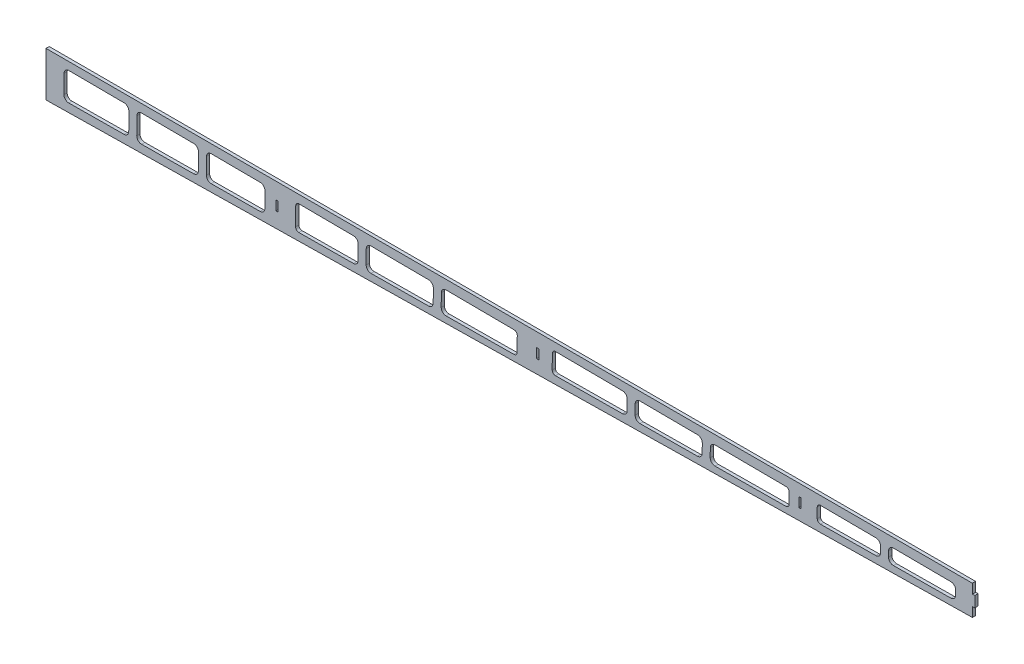
SolidWorks part; units mm, degrees
ref_plane "前视基准面" through (0, 0, 0) normal (0, 0, 1) x (1, 0, 0)
ref_plane "上视基准面" through (0, 0, 0) normal (0, 1, 0) x (1, 0, 0)
ref_plane "右视基准面" through (0, 0, 0) normal (1, 0, 0) x (0, 0, -1)
sketch "Model" plane through (0, 0, 0) normal (0, 0, 1) x (1, 0, 0)
  line L0 (785.4351, -35.5339) -> (785.4351, -41.4469)
  line L1 (786.9351, -41.4469) -> (786.9351, -48.1474)
  line L2 (786.9351, -48.1474) -> (785.4351, -48.1474)
  line L3 (206.6001, -35.5339) -> (206.6001, -63.4755)
  line L4 (350.2005, -45.6437) -> (350.2005, -51.6437)
  line L5 (513.2012, -44.1523) -> (513.2012, -50.1523)
  line L6 (676.9838, -42.8438) -> (676.9838, -48.8438)
  line L7 (206.6001, -35.5339) -> (351.5037, -35.5339)
  line L8 (351.5037, -35.5339) -> (514.2811, -35.5339)
  line L9 (514.2811, -35.5339) -> (677.8391, -35.5339)
  line L10 (677.8391, -35.5339) -> (785.4351, -35.5339)
  line L11 (206.6001, -63.4755) -> (785.4665, -54.0699)
  line L12 (786.9351, -41.4469) -> (785.4351, -41.4469)
  line L13 (676.9838, -42.8438) -> (678.4838, -42.8438)
  line L14 (678.4838, -42.8438) -> (678.4838, -48.8438)
  line L15 (676.9838, -48.8438) -> (678.4838, -48.8438)
  line L16 (513.2012, -44.1523) -> (514.7012, -44.1523)
  line L17 (514.7012, -44.1523) -> (514.7012, -50.1523)
  line L18 (513.2012, -50.1523) -> (514.7012, -50.1523)
  line L19 (350.2005, -45.6437) -> (351.7005, -45.6437)
  line L20 (351.7005, -45.6437) -> (351.7005, -51.6437)
  line L21 (350.2005, -51.6437) -> (351.7005, -51.6437)
  line L22 (255.3856, -40.6006) -> (220.8863, -40.3916)
  line L23 (255.3284, -57.6646) -> (220.8258, -57.9857)
  line L24 (343.3766, -44.1337) -> (343.3174, -53.8918)
  line L25 (217.8682, -43.3734) -> (217.7979, -54.9676)
  line L26 (266.3848, -40.6673) -> (298.8842, -40.8641)
  line L27 (266.3286, -57.5622) -> (298.831, -57.2598)
  line L28 (309.8832, -40.9308) -> (340.3948, -41.1156)
  line L29 (309.831, -57.1574) -> (340.3454, -56.8735)
  line L30 (364.652, -40.6438) -> (398.7222, -40.8811)
  line L31 (409.7112, -40.9577) -> (445.6232, -41.2078)
  line L32 (456.6128, -41.2844) -> (499.0688, -41.5801)
  line L33 (362.6382, -42.6298) -> (362.5578, -54.1645)
  line L34 (364.5764, -56.1783) -> (398.6668, -55.8602)
  line L35 (409.665, -55.7575) -> (445.5731, -55.4223)
  line L36 (456.5713, -55.3197) -> (499.0084, -54.9236)
  line L37 (501.0548, -43.594) -> (500.9897, -52.9376)
  line L38 (406.618, -55.8674) -> (406.6186, -55.7859)
  line L39 (524.9663, -40.4255) -> (566.7724, -40.7168)
  line L40 (577.7722, -40.7934) -> (613.674, -41.0435)
  line L41 (624.6738, -41.1201) -> (668.9628, -41.4286)
  line L42 (524.9077, -53.5082) -> (566.7407, -53.1177)
  line L43 (577.7416, -53.0151) -> (613.647, -52.6799)
  line L44 (624.6479, -52.5772) -> (668.9206, -52.164)
  line L45 (522.8891, -51.4943) -> (522.9524, -42.4115)
  line L46 (670.9488, -43.4425) -> (670.9019, -50.178)
  line L47 (690.4954, -40.8692) -> (725.1012, -41.1103)
  line L48 (736.095, -41.1869) -> (772.0021, -41.437)
  line L49 (690.4954, -51.0729) -> (725.0829, -50.7501)
  line L50 (736.0811, -50.6474) -> (771.9892, -50.3123)
  line L51 (688.4815, -42.8553) -> (688.4767, -49.0714)
  line L52 (774.9812, -44.4578) -> (774.9611, -47.3333)
  line L53 (785.4665, -54.0699) -> (785.4351, -48.1474)
  line L54 (258.3004, -54.6829) -> (258.3674, -43.6187)
  line L55 (263.3667, -43.649) -> (263.3007, -54.5442)
  line L56 (301.866, -43.8823) -> (301.803, -54.2781)
  line L57 (306.8032, -54.1394) -> (306.8651, -43.9125)
  line L58 (401.7012, -43.9019) -> (401.6387, -52.8812)
  line L59 (406.637, -52.7395) -> (406.6903, -43.9394)
  line L60 (448.6022, -44.2287) -> (448.545, -52.4434)
  line L61 (453.5433, -52.3017) -> (453.592, -44.2661)
  line L62 (569.7514, -43.7349) -> (569.7127, -50.1187)
  line L63 (574.7513, -43.7751) -> (574.7136, -49.997)
  line L64 (616.6531, -44.0616) -> (616.6189, -49.6982)
  line L65 (621.653, -44.1019) -> (621.6199, -49.5592)
  line L66 (728.0802, -44.1311) -> (728.0548, -47.7711)
  line L67 (733.0741, -44.1686) -> (733.0532, -47.6294)
  arc A0 (255.3284, -57.6646) -> (258.3004, -54.6829) centre (255.3004, -54.6647) ccw
  arc A1 (340.3454, -56.8735) -> (343.3174, -53.8918) centre (340.3175, -53.8736) ccw
  arc A2 (217.7979, -54.9676) -> (220.8258, -57.9857) centre (220.7979, -54.9858) ccw
  arc A3 (343.3766, -44.1337) -> (340.3948, -41.1156) centre (340.3766, -44.1156) ccw
  arc A4 (220.8863, -40.3916) -> (217.8682, -43.3734) centre (220.8681, -43.3916) ccw
  arc A5 (258.3674, -43.6187) -> (255.3856, -40.6006) centre (255.3675, -43.6006) ccw
  arc A6 (266.3848, -40.6673) -> (263.3667, -43.649) centre (266.3667, -43.6672) ccw
  arc A7 (298.831, -57.2598) -> (301.803, -54.2781) centre (298.8031, -54.2599) ccw
  arc A8 (301.866, -43.8823) -> (298.8842, -40.8641) centre (298.8661, -43.8641) ccw
  arc A9 (263.3007, -54.5442) -> (266.3286, -57.5622) centre (266.3007, -54.5624) ccw
  arc A10 (309.8832, -40.9308) -> (306.8651, -43.9125) centre (309.8651, -43.9307) ccw
  arc A11 (306.8032, -54.1394) -> (309.831, -57.1574) centre (309.8031, -54.1575) ccw
  arc A12 (364.652, -40.6438) -> (362.6382, -42.6298) centre (364.6381, -42.6437) ccw
  arc A13 (362.5578, -54.1645) -> (364.5764, -56.1783) centre (364.5578, -54.1784) ccw
  arc A14 (499.0084, -54.9236) -> (500.9897, -52.9376) centre (498.9898, -52.9237) ccw
  arc A15 (401.7012, -43.9019) -> (398.7222, -40.8811) centre (398.7013, -43.881) ccw
  arc A16 (398.6668, -55.8602) -> (401.6387, -52.8812) centre (398.6388, -52.8603) ccw
  arc A17 (409.7112, -40.9577) -> (406.6903, -43.9394) centre (409.6903, -43.9576) ccw
  arc A18 (406.637, -52.7395) -> (409.665, -55.7575) centre (409.637, -52.7576) ccw
  arc A19 (448.6022, -44.2287) -> (445.6232, -41.2078) centre (445.6023, -44.2078) ccw
  arc A20 (445.5731, -55.4223) -> (448.545, -52.4434) centre (445.5451, -52.4225) ccw
  arc A21 (456.6128, -41.2844) -> (453.592, -44.2661) centre (456.592, -44.2843) ccw
  arc A22 (453.5433, -52.3017) -> (456.5713, -55.3197) centre (456.5433, -52.3198) ccw
  arc A23 (501.0548, -43.594) -> (499.0688, -41.5801) centre (499.0549, -43.5801) ccw
  arc A24 (670.9488, -43.4425) -> (668.9628, -41.4286) centre (668.9488, -43.4286) ccw
  arc A25 (524.9663, -40.4255) -> (522.9524, -42.4115) centre (524.9523, -42.4255) ccw
  arc A26 (522.8891, -51.4943) -> (524.9077, -53.5082) centre (524.8891, -51.5083) ccw
  arc A27 (668.9206, -52.164) -> (670.9019, -50.178) centre (668.9019, -50.1641) ccw
  arc A28 (569.7514, -43.7349) -> (566.7724, -40.7168) centre (566.7515, -43.7167) ccw
  arc A29 (566.7407, -53.1177) -> (569.7127, -50.1187) centre (566.7127, -50.1179) ccw
  arc A30 (577.7722, -40.7934) -> (574.7513, -43.7751) centre (577.7513, -43.7933) ccw
  arc A31 (574.7136, -49.997) -> (577.7416, -53.0151) centre (577.7136, -50.0152) ccw
  arc A32 (613.647, -52.6799) -> (616.6189, -49.6982) centre (613.619, -49.6801) ccw
  arc A33 (616.6531, -44.0616) -> (613.674, -41.0435) centre (613.6531, -44.0434) ccw
  arc A34 (624.6738, -41.1201) -> (621.653, -44.1019) centre (624.6529, -44.12) ccw
  arc A35 (621.6199, -49.5592) -> (624.6479, -52.5772) centre (624.6199, -49.5774) ccw
  arc A36 (690.4954, -40.8692) -> (688.4815, -42.8553) centre (690.4815, -42.8692) ccw
  arc A37 (688.4767, -49.0714) -> (690.4954, -51.0729) centre (690.4767, -49.073) ccw
  arc A38 (728.0802, -44.1311) -> (725.1012, -41.1103) centre (725.0803, -44.1102) ccw
  arc A39 (725.0829, -50.7501) -> (728.0548, -47.7711) centre (725.0549, -47.7502) ccw
  arc A40 (736.095, -41.1869) -> (733.0741, -44.1686) centre (736.0741, -44.1868) ccw
  arc A41 (733.0532, -47.6294) -> (736.0811, -50.6474) centre (736.0531, -47.6475) ccw
  arc A42 (771.9892, -50.3123) -> (774.9611, -47.3333) centre (771.9612, -47.3124) ccw
  arc A43 (774.9812, -44.4578) -> (772.0021, -41.437) centre (771.9812, -44.4369) ccw
extrude "凸台-拉伸1" add sketch "Model" along normal blind 2
